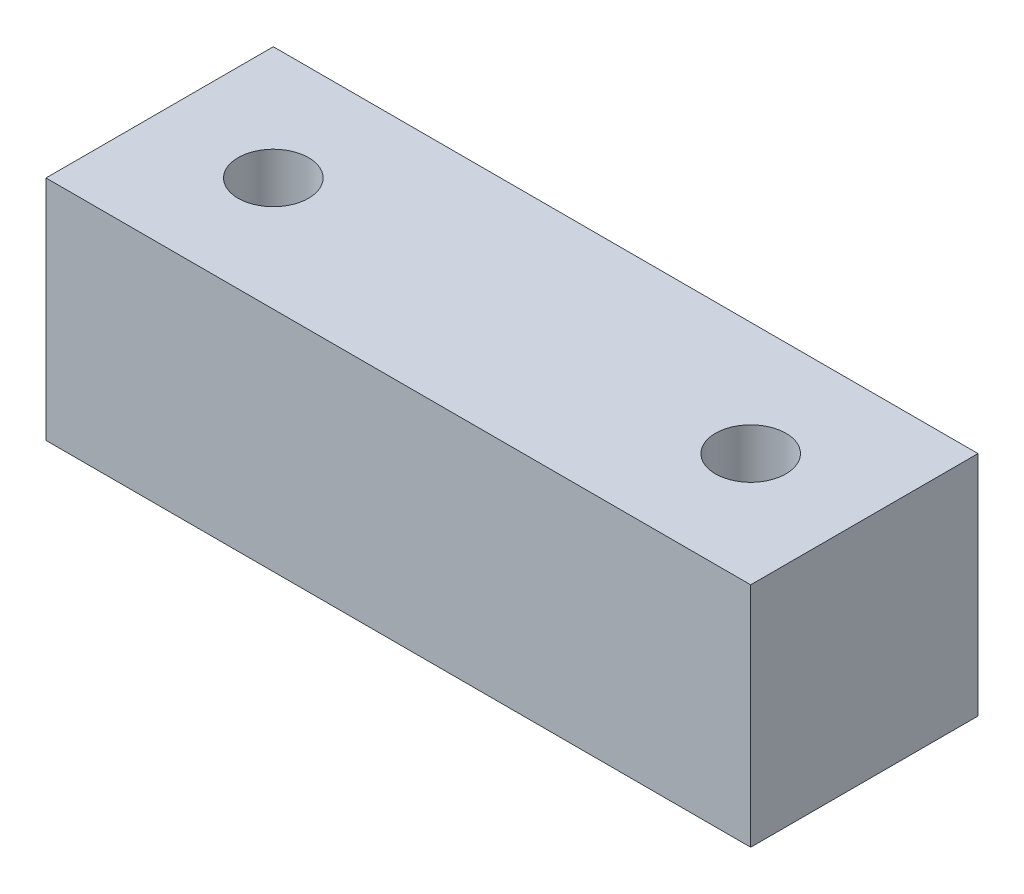
SolidWorks part; units mm, degrees
material "炭素鋼(普通)"
ref_plane "正面" through (0, 0, 0) normal (0, 0, 1) x (1, 0, 0)
ref_plane "平面" through (0, 0, 0) normal (0, 1, 0) x (1, 0, 0)
ref_plane "右側面" through (0, 0, 0) normal (1, 0, 0) x (0, 0, -1)
sketch "ｽｹｯﾁ1" plane through (0, 0, 0) normal (0, 1, 0) x (1, 0, 0)
  line L1 (-15.5, -5) -> (15.5, -5)
  line L2 (-15.5, -5) -> (-15.5, 5)
  line L3 (-15.5, 5) -> (15.5, 5)
  line L4 (15.5, -5) -> (15.5, 5)
  line L5 (-15.5, -5) -> (15.5, 5) construction
  line L6 (-15.5, 5) -> (15.5, -5) construction
  point P0 (0, 0)
  dimension "D1" = 31
  dimension "D2" = 10
extrude "ﾎﾞｽ - 押し出し1" add sketch "ｽｹｯﾁ1" along normal blind 10
sketch "ｽｹｯﾁ2" plane through (0, 10, 0) normal (0, 1, 0) x (1, 0, 0)
  line L0 (-10.5, 0) -> (10.5, 0) construction
  line L1 (0, 0) -> (0, 5) construction
  line L2 (15.5, 5) -> (-15.5, 5) construction
  circle A0 centre (-10.5, 0) radius 1.55
  circle A1 centre (10.5, 0) radius 1.55
  dimension "D2" = 3.1
  dimension "D1" = 21
extrude "ｶｯﾄ - 押し出し1" cut sketch "ｽｹｯﾁ2" against normal through all
